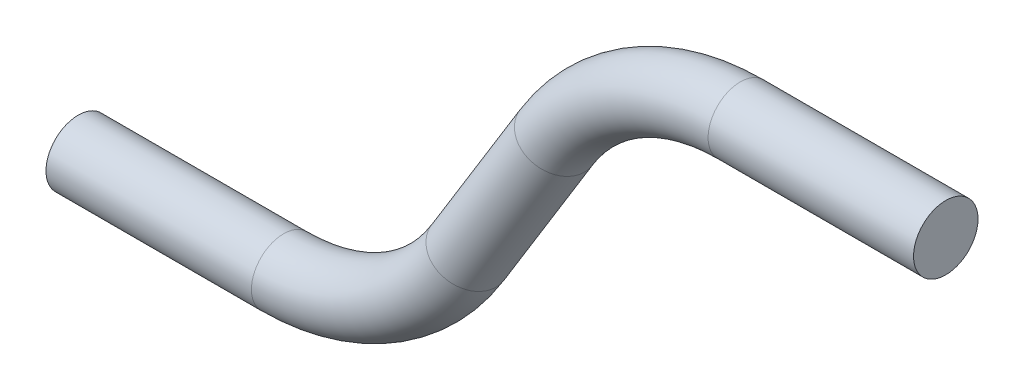
SolidWorks part; units mm, degrees
ref_plane "Front Plane" through (0, 0, 0) normal (0, 0, 1) x (1, 0, 0)
ref_plane "Top Plane" through (0, 0, 0) normal (0, 1, 0) x (1, 0, 0)
ref_plane "Right Plane" through (0, 0, 0) normal (1, 0, 0) x (0, 0, -1)
ref_plane "平面1" through (0, -4.4248, -66.3717) normal (0, -0.0665, -0.9978) x (-1, 0, 0)
sketch "ｽｹｯﾁ2" plane through (0, -4.4248, -66.3717) normal (0, -0.0665, -0.9978) x (-1, 0, 0)
  line L0 (123.0431, 39.5123) -> (136.7431, 39.5123)
  line L1 (123.0431, 43.2623) -> (123.0431, 35.7623) construction
  line L2 (148.5716, 32.745) -> (153.8715, 23.7296)
  line L3 (165.7, 16.9623) -> (179.4, 16.9623)
  line L4 (179.4, 13.2123) -> (179.4, 20.7123) construction
  line L5 (166.7, 25.9623) -> (166.7, 7.9623) construction
  line L6 (135.7431, 30.5123) -> (135.7431, 48.5123) construction
  arc A0 (136.7431, 39.5123) -> (148.5716, 32.745) centre (136.7431, 25.7913) cw
  arc A1 (153.8715, 23.7296) -> (165.7, 16.9623) centre (165.7, 30.6834) ccw
  dimension "D1" = 1
  dimension "D2" = 1
ref_plane "平面2" through (-179.4, 0, 0) normal (1, 0, 0) x (0, 0, -1)
sketch "ｽｹｯﾁ3" plane through (-179.4, 0, 0) normal (1, 0, 0) x (0, 0, -1)
  circle A0 centre (67.5, 12.5) radius 2.15
  dimension "D1" = 4.3
sweep "ｽｲｰﾌﾟ1" add profiles "ｽｹｯﾁ3" path "ｽｹｯﾁ2"
